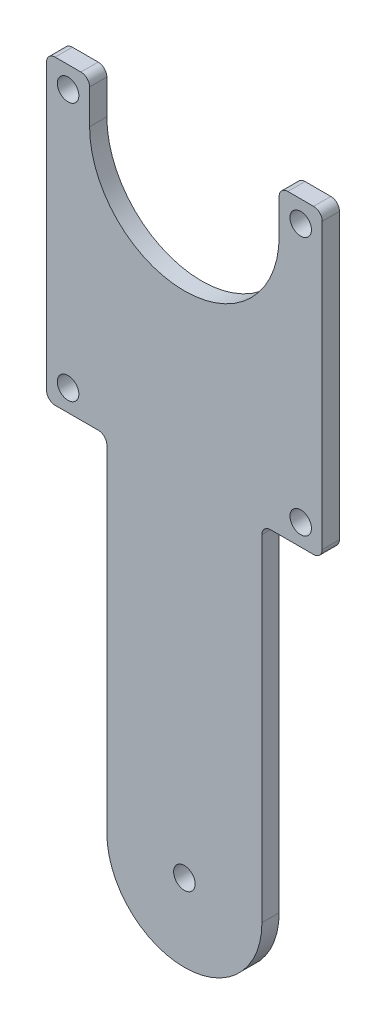
SolidWorks part; units mm, degrees
material "自訂玻璃纖維"
ref_plane "前基準面" through (0, 0, 0) normal (0, 0, 1) x (1, 0, 0)
ref_plane "上基準面" through (0, 0, 0) normal (0, 1, 0) x (1, 0, 0)
ref_plane "右基準面" through (0, 0, 0) normal (1, 0, 0) x (0, 0, -1)
sketch "草圖1" plane through (0, 0, 0) normal (0, 0, 1) x (1, 0, 0)
  line L0 (23.0486, -20.4042) -> (18.0486, -20.4042)
  line L1 (-7.9514, -2.4042) -> (-7.9514, -15.4042)
  line L2 (24.0486, -15.4042) -> (24.0486, -2.4042)
  line L3 (24.0486, -15.4042) -> (24.0486, -19.4042)
  line L4 (-7.9514, -15.4042) -> (-7.9514, -19.4042)
  line L5 (17.0486, -60.4042) -> (17.0486, -21.4042)
  line L6 (-0.9514, -60.4042) -> (-0.9514, -21.4042)
  line L7 (-3.9514, 14.5958) -> (-6.9514, 14.5958)
  line L8 (-1.9514, -20.4042) -> (-6.9514, -20.4042)
  line L9 (23.0486, 14.5958) -> (20.0486, 14.5958)
  line L10 (24.0486, -2.4042) -> (24.0486, 13.5958)
  line L11 (-7.9514, 13.5958) -> (-7.9514, -2.4042)
  line L13 (19.0486, 13.5958) -> (19.0486, 9.5958)
  line L15 (-2.9514, 13.5958) -> (-2.9514, 9.5958)
  circle A0 centre (-5.4514, -17.9042) radius 1.25
  circle A1 centre (21.5486, -17.9042) radius 1.25
  arc A2 (-6.9514, 14.5958) -> (-7.9514, 13.5958) centre (-6.9514, 13.5958) ccw
  arc A3 (23.0486, 14.5958) -> (24.0486, 13.5958) centre (23.0486, 13.5958) cw
  arc A4 (17.0486, -60.4042) -> (-0.9514, -60.4042) centre (8.0486, -60.4042) cw
  arc A5 (-6.9514, -20.4042) -> (-7.9514, -19.4042) centre (-6.9514, -19.4042) cw
  arc A6 (23.0486, -20.4042) -> (24.0486, -19.4042) centre (23.0486, -19.4042) ccw
  arc A7 (-0.9514, -21.4042) -> (-1.9514, -20.4042) centre (-1.9514, -21.4042) ccw
  arc A8 (17.0486, -21.4042) -> (18.0486, -20.4042) centre (18.0486, -21.4042) cw
  circle A9 centre (-5.4514, 12.0958) radius 1.25
  circle A10 centre (21.5486, 12.0958) radius 1.25
  circle A11 centre (8.0486, -60.4042) radius 1.25
  arc A12 (-2.9514, 9.5958) -> (19.0486, 9.5958) centre (8.0486, 9.5958) ccw
  arc A13 (-3.9514, 14.5958) -> (-2.9514, 13.5958) centre (-3.9514, 13.5958) cw
  arc A14 (20.0486, 14.5958) -> (19.0486, 13.5958) centre (20.0486, 13.5958) ccw
  point P23 (-0.9514, -20.4042)
  point P26 (17.0486, -20.4042)
  point P31 (8.0486, -60.4042)
  point P41 (8.0486, 9.5958)
  dimension "D3" = 2.5
  dimension "D4" = 2.5
  dimension "D5" = 27
  dimension "D7" = 2.5
  dimension "D10" = 40
  dimension "D13" = 35
  dimension "D11" = 2.5
  dimension "D2" = 1
  dimension "D8" = 9
  dimension "D9" = 1
  dimension "D12" = 1
  dimension "D14" = 2.5
  dimension "D15" = 2.5
  dimension "D16" = 2.5
  dimension "D19" = 1
  dimension "D6" = 13
  dimension "D17" = 22
  dimension "D18" = 5
extrude "填料-伸長1" add sketch "草圖1" along normal blind 2
